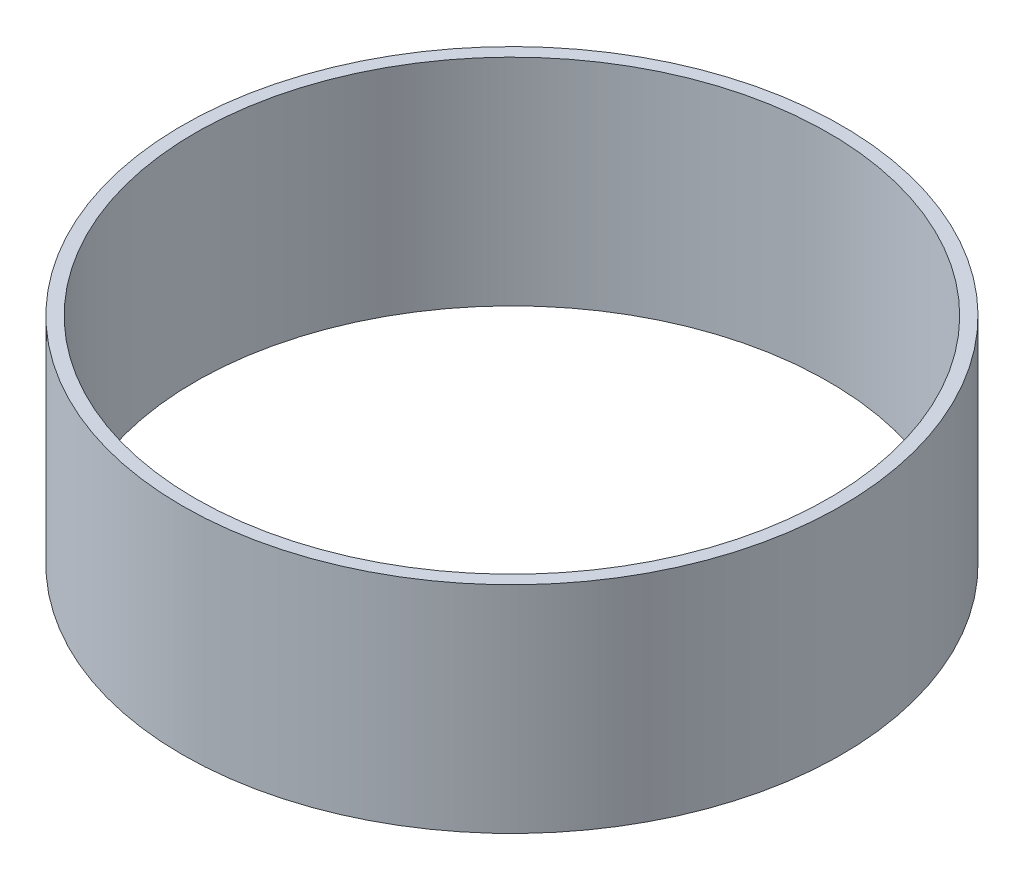
SolidWorks part; units mm, degrees
material "Медь"
ref_plane "Спереди" through (0, 0, 0) normal (0, 0, 1) x (1, 0, 0)
ref_plane "Сверху" through (0, 0, 0) normal (0, 1, 0) x (1, 0, 0)
ref_plane "Справа" through (0, 0, 0) normal (1, 0, 0) x (0, 0, -1)
sketch "Эскиз1" plane through (0, 0, 0) normal (0, 1, 0) x (1, 0, 0)
  circle A0 centre (0, 0) radius 7.35
  circle A1 centre (0, 0) radius 7.65
  dimension "D1" = 14.7
  dimension "D2" = 0.3
extrude "Бобышка-Вытянуть1" add sketch "Эскиз1" along normal blind 5
